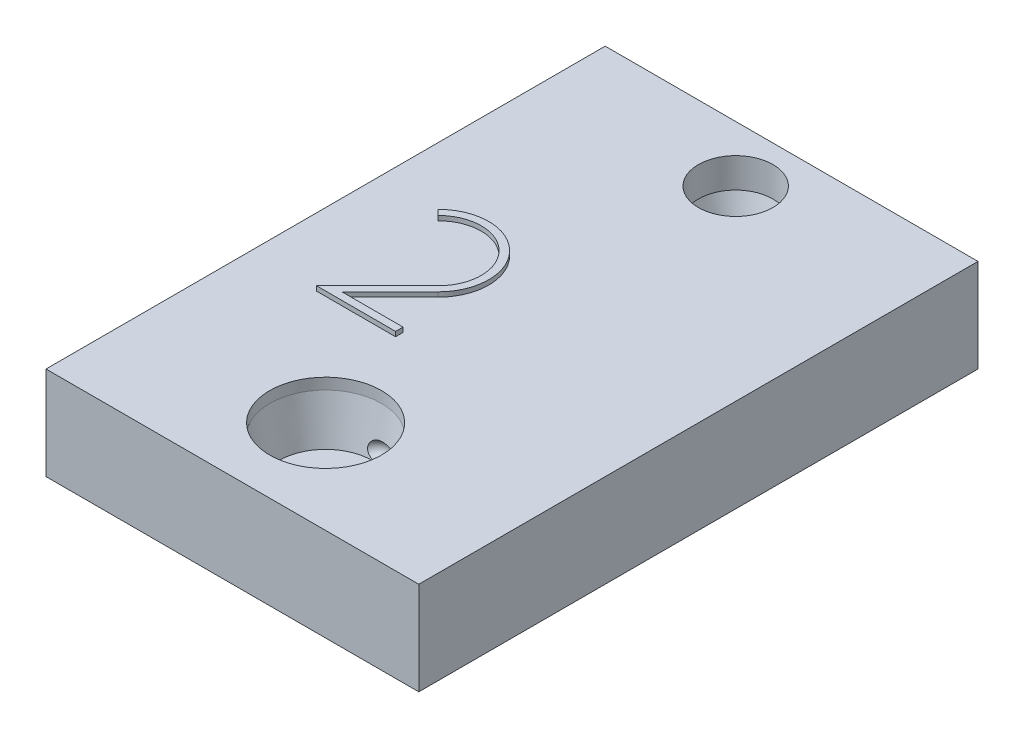
SolidWorks part; units mm, degrees
ref_plane "Front Plane" through (0, 0, 0) normal (0, 0, 1) x (1, 0, 0)
ref_plane "Top Plane" through (0, 0, 0) normal (0, 1, 0) x (1, 0, 0)
ref_plane "Right Plane" through (0, 0, 0) normal (1, 0, 0) x (0, 0, -1)
sketch "Sketch1" plane through (0, 0, 0) normal (0, 0, 1) x (1, 0, 0)
  line L1 (-20, 5) -> (20, 5)
  line L2 (-20, 5) -> (-20, -5)
  line L3 (-20, -5) -> (20, -5)
  line L4 (20, 5) -> (20, -5)
  line L5 (-20, 5) -> (20, -5) construction
  line L6 (-20, -5) -> (20, 5) construction
  point P0 (0, 0)
  dimension "D1" = 10
  dimension "D2" = 40
extrude "Boss-Extrude1" add sketch "Sketch1" along normal blind 60
ref_plane "Plane1" through (0, 0, 0) normal (0, 1, 0) x (1, 0, 0)
sketch "Sketch2" plane through (0, 0, 0) normal (0, 1, 0) x (1, 0, 0)
  line L1 (-20, -60) -> (20, -60) construction
  line L5 (0, -50) -> (0, -46)
  line L6 (1, -45) -> (15, -45)
  line L7 (15, -42) -> (0, -42)
  line L8 (0, -42) -> (-15, -42)
  line L9 (-15, -39) -> (15, -39)
  line L10 (15, -36) -> (-15, -36)
  line L11 (-15, -33) -> (15.3556, -33)
  line L12 (15.3556, -30) -> (-15, -30)
  line L13 (-15, -27) -> (15, -27)
  line L14 (15, -24) -> (-15, -24)
  line L15 (-15, -21) -> (15, -21)
  line L16 (15, -18) -> (-15, -18)
  line L17 (-15, -15) -> (15, -15)
  line L18 (15, -12) -> (1, -12)
  line L19 (0, -11) -> (0, -6)
  arc A0 (15, -45) -> (15, -42) centre (15, -43.5) ccw
  arc A1 (-15, -42) -> (-15, -39) centre (-15, -40.5) cw
  arc A2 (15, -39) -> (15, -36) centre (15, -37.5) ccw
  arc A3 (-15, -36) -> (-15, -33) centre (-15, -34.5) cw
  arc A4 (15.3556, -33) -> (15.3556, -30) centre (15.3556, -31.5) ccw
  arc A5 (-15, -30) -> (-15, -27) centre (-15, -28.5) cw
  arc A6 (15, -27) -> (15, -24) centre (15, -25.5) ccw
  arc A7 (-15, -24) -> (-15, -21) centre (-15, -22.5) cw
  arc A8 (15, -21) -> (15, -18) centre (15, -19.5) ccw
  arc A9 (-15, -18) -> (-15, -15) centre (-15, -16.5) cw
  arc A10 (15, -15) -> (15, -12) centre (15, -13.5) ccw
  arc A11 (0, -46) -> (1, -45) centre (1, -46) cw
  arc A12 (1, -12) -> (0, -11) centre (1, -11) cw
  point P5 (0, -45)
  point P9 (0, -12)
  dimension "D5" = 1
  dimension "D1" = 10
  dimension "D2" = 5
  dimension "D3" = 15
  dimension "D4" = 15
  dimension "D16" = 6
ref_plane "Plane2" through (0, 0, 6) normal (0, 0, -1) x (-1, 0, 0)
sketch "Sketch10" plane through (0, 0, 6) normal (0, 0, -1) x (-1, 0, 0)
  circle A0 centre (0, 0) radius 1
  dimension "D1" = 2
sketch "Sketch11" plane through (0, 0, 6) normal (0, 0, -1) x (-1, 0, 0)
sweep "Cut-Sweep1" cut profiles "Sketch10" path "Sketch2"
ref_plane "Plane4" through (0, 0, 0) normal (1, 0, 0) x (0, 0, -1)
sketch "Sketch13" plane through (0, 0, 0) normal (1, 0, 0) x (0, 0, -1)
  line L0 (-50, -1) -> (-55, -1)
  line L2 (-50, -1) -> (-50, 29)
  line L3 (-50, 29) -> (-56, 29)
  line L4 (-56, 29) -> (-56, 3.8)
  line L5 (-56, 3.8) -> (-55, -1)
  dimension "D1" = 5
  dimension "D3" = 6
  dimension "D4" = 30
revolve "Cut-Revolve1" cut sketch "Sketch13" angle 360 about L2
sketch "Sketch14" plane through (0, 0, 0) normal (1, 0, 0) x (0, 0, -1)
  line L0 (-6, -1) -> (-3, -1)
  line L2 (-6, -1) -> (-6, 29)
  line L3 (-6, 29) -> (-2, 29)
  line L4 (-2, 29) -> (-2, 1.8)
  line L5 (-2, 1.8) -> (-3, -1)
  dimension "D1" = 3
  dimension "D3" = 30
  dimension "D4" = 4
revolve "Cut-Revolve2" cut sketch "Sketch14" angle 360 about L2
sketch "Sketch15" plane through (0, 5, 0) normal (0, 1, 0) x (1, 0, 0)
  line L0 (-20, -30) -> (20, -30) construction
  line L1 (-20, -60) -> (-20, 0) construction
  line L2 (20, -60) -> (20, 0) construction
  line L3 (-4.2417, -38.2508) -> (-12.7251, -38.2508)
  line L4 (-12.7251, -38.2508) -> (-6.1942, -31.7199)
  line L5 (-4.2417, -37.4508) -> (-10.7937, -37.4508)
  line L6 (-10.7937, -37.4508) -> (-5.6285, -32.2856)
  line L7 (-13.2908, -24.6234) -> (-12.7251, -25.1891)
  line L8 (-4.2417, -37.4508) -> (-4.2417, -38.2508)
  arc A0 (-6.1942, -31.7199) -> (-12.7251, -25.1891) centre (-9.4597, -28.4545) ccw
  arc A1 (-5.6285, -32.2856) -> (-13.2908, -24.6234) centre (-9.4597, -28.4545) ccw
  dimension "D1" = 0.8
extrude "Boss-Extrude2" add sketch "Sketch15" along normal blind 0.5
